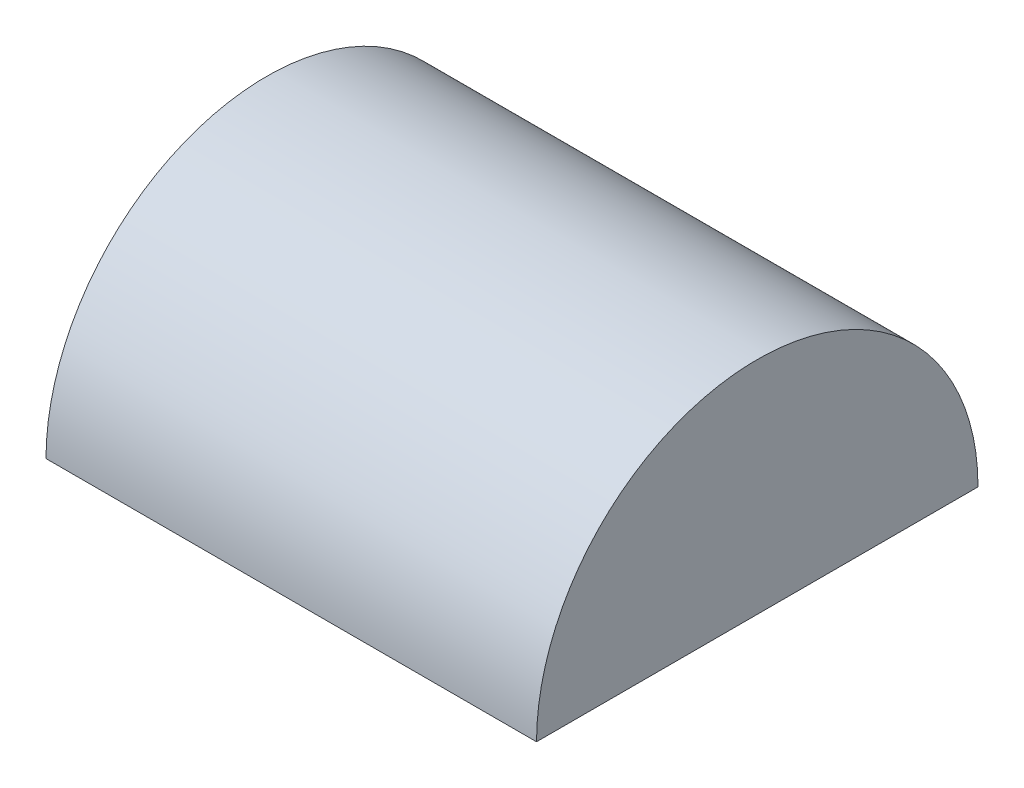
SolidWorks part; units mm, degrees
ref_plane "前视基准面" through (0, 0, 0) normal (0, 0, 1) x (1, 0, 0)
ref_plane "上视基准面" through (0, 0, 0) normal (0, 1, 0) x (1, 0, 0)
ref_plane "右视基准面" through (0, 0, 0) normal (1, 0, 0) x (0, 0, -1)
sketch "草图1" plane through (0, 0, 0) normal (1, 0, 0) x (0, 0, -1)
  line L0 (-36, 0) -> (36, 0)
  arc A0 (36, 0) -> (-36, 0) centre (0, 0) ccw
  dimension "D1" = 72
extrude "凸台-拉伸1" add sketch "草图1" along normal blind 80
